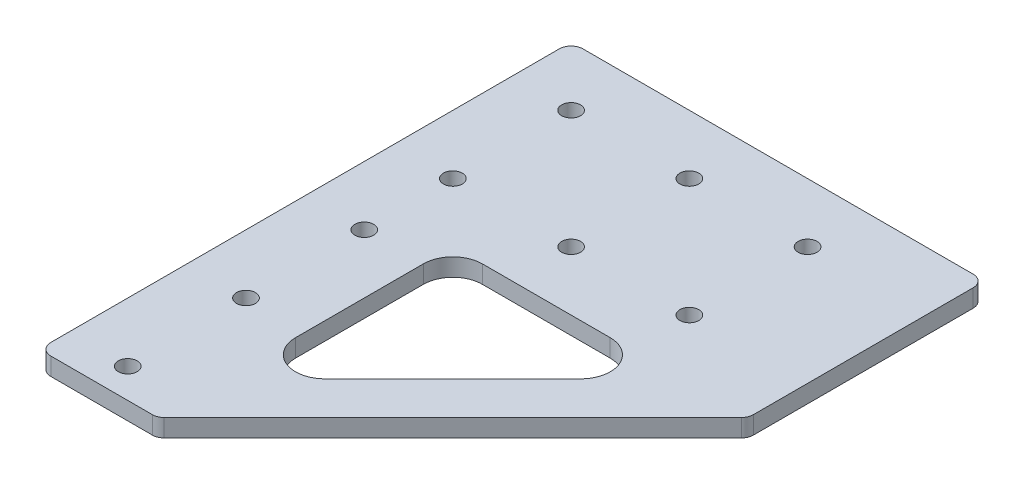
SolidWorks part; units mm, degrees
material "Thornel Mat VMA"
ref_plane "前视基准面" through (0, 0, 0) normal (0, 0, 1) x (1, 0, 0)
ref_plane "上视基准面" through (0, 0, 0) normal (0, 1, 0) x (1, 0, 0)
ref_plane "右视基准面" through (0, 0, 0) normal (1, 0, 0) x (0, 0, -1)
other "Configuration Table"
sketch "草图1" plane through (0, 0, 0) normal (0, 1, 0) x (1, 0, 0)
  line L0 (0, 0) -> (0, -50) construction
  line L1 (0, -50) -> (-20, -50)
  line L2 (-20, -50) -> (-20, 40)
  line L3 (-20, 40) -> (50, 40)
  line L4 (50, 40) -> (50, 0)
  line L5 (50, 0) -> (0, 0) construction
  line L6 (0, -50) -> (50, 0)
  line L7 (0, -38.6863) -> (0, 0)
  line L8 (0, 0) -> (38.6863, 0)
  line L9 (38.6863, 0) -> (0, -38.6863)
  circle A0 centre (-10, -5) radius 1.6
  circle A1 centre (-10, -25) radius 1.6
  circle A2 centre (-10, -45) radius 1.6
  circle A3 centre (-10, 10) radius 1.6
  circle A4 centre (-10, 30) radius 1.6
  circle A5 centre (10, 30) radius 1.6
  circle A6 centre (10, 10) radius 1.6
  circle A7 centre (30, 30) radius 1.6
  circle A8 centre (30, 10) radius 1.6
  dimension "D8" = 3.2
  dimension "D1" = 40
  dimension "D2" = 20
  dimension "D3" = 50
  dimension "D4" = 50
  dimension "D5" = 8
  dimension "D6" = 10
  dimension "D7" = 5
  dimension "D10" = 20
  dimension "D11" = 10
  dimension "D12" = 10
  dimension "D13" = 10
  dimension "D15" = 20
  dimension "D9" = 3
  dimension "D14" = 3
extrude "凸台-拉伸1" add sketch "草图1" along normal blind 3
fillet "圆角1" radius 2 5 edges at (-20, 1.5, 50) (-20, 1.5, -40) (50, 1.5, -40) (50, 1.5, 0) (0, 1.5, 50)
fillet "圆角2" radius 5 3 edges at (0, 1.5, 0) (0, 1.5, 38.6863) (38.6863, 1.5, 0)
ref_plane "基准面1" through (-20, 0, 0) normal (1, 0, 0) x (0, 0, -1)
